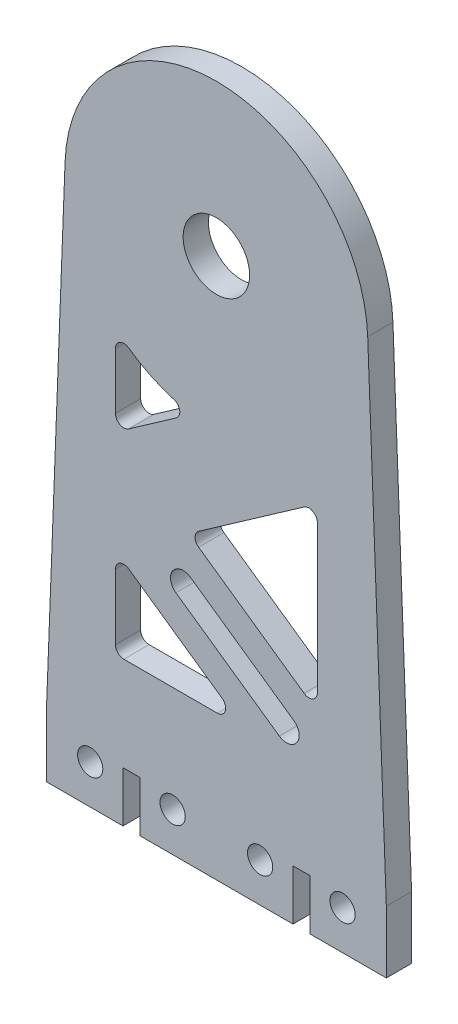
SolidWorks part; units mm, degrees
material "Acrylic (Medium-high impact)"
ref_plane "Front Plane" through (0, 0, 0) normal (0, 0, 1) x (1, 0, 0)
ref_plane "Top Plane" through (0, 0, 0) normal (0, 1, 0) x (1, 0, 0)
ref_plane "Right Plane" through (0, 0, 0) normal (1, 0, 0) x (0, 0, -1)
sketch "Sketch1" plane through (0, 0, 0) normal (0, 0, 1) x (1, 0, 0)
  line L0 (-11.1, 83.4741) -> (-9.1, 83.4741) construction
  line L1 (0, 41.6741) -> (20.2, 41.6741) construction
  line L2 (20.2, 41.6741) -> (20.2, 83.4741) construction
  line L3 (0, 83.4741) -> (9.1, 83.4741)
  line L4 (10.1, 83.4741) -> (10.1, 41.6741) construction
  line L5 (0, 62.5741) -> (20.2, 62.5741) construction
  line L6 (-20.2, 83.4741) -> (-20.2, 41.6741) construction
  line L7 (-20.2, 41.6741) -> (0, 41.6741) construction
  line L8 (-20.2, 83.4741) -> (-11.1, 83.4741)
  line L9 (-10.1, 83.4741) -> (-10.1, 41.6741) construction
  line L10 (-20.2, 62.5741) -> (0, 62.5741) construction
  line L11 (-20.2, 41.6741) -> (-17.9755, -0.9384) construction
  line L12 (20.2, 41.6741) -> (17.9755, -0.9384) construction
  line L13 (0, 0) -> (0, 147.6909) construction
  line L14 (-20.2, 90.8741) -> (-17.9867, 148.3831)
  line L15 (20.2, 90.8741) -> (17.9867, 148.3831)
  line L16 (11.1, 83.4741) -> (20.2, 83.4741)
  line L17 (-11.1, 83.4741) -> (-11.1, 89.4741)
  line L18 (-11.1, 89.4741) -> (-9.1, 89.4741)
  line L19 (-9.1, 83.4741) -> (-9.1, 89.4741)
  line L20 (11.1, 83.4741) -> (9.1, 83.4741) construction
  line L21 (11.1, 83.4741) -> (11.1, 89.4741)
  line L22 (11.1, 89.4741) -> (9.1, 89.4741)
  line L23 (9.1, 83.4741) -> (9.1, 89.4741)
  line L24 (-9.1, 83.4741) -> (0, 83.4741)
  line L25 (-20.2, 90.8741) -> (20.2, 90.8741) construction
  line L26 (-20.2, 83.4741) -> (-20.2, 90.8741)
  line L27 (20.2, 83.4741) -> (20.2, 90.8741)
  circle A0 centre (10.1, 73.3741) radius 6.5 construction
  arc A1 (-17.9755, -0.9384) -> (17.9755, -0.9384) centre (0, 0) cw construction
  circle A2 centre (0, 0) radius 2.5 construction
  arc A3 (-17.9755, -0.9384) -> (17.9755, -0.9384) centre (0, 0) ccw construction
  circle A4 centre (5.2, 88.1241) radius 1.5
  circle A5 centre (15, 88.1241) radius 1.5
  circle A6 centre (-10.1, 51.7741) radius 6.5 construction
  circle A7 centre (-15, 88.1241) radius 1.5
  circle A8 centre (-5.2, 88.1241) radius 1.5
  circle A9 centre (-15, 37.0241) radius 1.5 construction
  circle A10 centre (-5.2, 37.0241) radius 1.5 construction
  circle A11 centre (0, 0) radius 52.75 construction
  circle A12 centre (5.2, 37.0241) radius 1.5 construction
  circle A13 centre (15, 37.0241) radius 1.5 construction
  arc A14 (17.9867, 148.3831) -> (-17.9867, 148.3831) centre (0, 147.6909) ccw
  circle A15 centre (0, 147.6909) radius 3.95
  circle A16 centre (10.1, 73.3741) radius 75 construction
  dimension "D1" = 5
  dimension "D2" = 18
  dimension "D10" = 51.1
  dimension "D3" = 13
  dimension "D4" = 3
  dimension "D8" = 9.8
  dimension "D9" = 105.5
  dimension "D5" = 20.2
  dimension "D19" = 36
  dimension "D20" = 7.9
  dimension "D18" = 150
  dimension "D6" = 10.1
  dimension "D7" = 41.8
  dimension "D13" = 10.1
  dimension "D14" = 6
  dimension "D15" = 9.8
  dimension "D16" = 2
  dimension "D21" = 7.4
extrude "Main Body Link B1" add sketch "Sketch1" along normal blind 3
sketch "Sketch2" plane through (0, 0, 3) normal (0, 0, 1) x (1, 0, 0)
  line L0 (0, 147.6909) -> (0, 83.4741) construction
  line L1 (-12, 134.2745) -> (12, 134.2745) construction
  line L2 (-12, 134.2745) -> (-12, 123.585)
  line L3 (-12, 100.6909) -> (3.2782, 100.6909)
  line L4 (12, 128.1722) -> (12, 106.7932)
  line L5 (-12, 117.4827) -> (12, 117.4827) construction
  line L6 (-12, 111.3804) -> (-12, 100.6909)
  line L7 (12, 100.6909) -> (-12, 117.4827) construction
  line L8 (-12, 117.4827) -> (12, 134.2745) construction
  line L9 (3.2782, 100.6909) -> (-12, 111.3804)
  line L10 (-12, 123.585) -> (-2.9299, 129.9309)
  line L12 (-3.2782, 117.4827) -> (12, 106.7932)
  line L13 (-3.2782, 117.4827) -> (12, 128.1722)
  line L14 (3.2782, 100.6909) -> (12, 100.6909) construction
  line L15 (12, 100.6909) -> (12, 106.7932) construction
  line L16 (-12, 123.585) -> (-12, 117.4827) construction
  line L17 (-12, 117.4827) -> (-12, 111.3804) construction
  line L19 (12, 134.2745) -> (12, 128.1722) construction
  line L20 (-9.1, 83.4741) -> (9.1, 83.4741) construction
  arc A0 (-12, 134.2745) -> (-2.9299, 129.9309) centre (0, 147.6909) ccw
  arc A1 (-17.9867, 148.3831) -> (-12, 134.2745) centre (0, 147.6909) ccw construction
  arc A2 (12, 134.2745) -> (17.9867, 148.3831) centre (0, 147.6909) ccw construction
  arc A3 (17.9867, 148.3831) -> (-17.9867, 148.3831) centre (0, 147.6909) ccw construction
  dimension "D1" = 24
  dimension "D2" = 47
  dimension "D3" = 10
extrude "Cut-Extrude1" cut sketch "Sketch2" against normal up to next contours L13 L12 L4 | A0 L2 L10 | L6 L3 L9
sketch "Sketch3" plane through (0, 0, 3) normal (0, 0, 1) x (1, 0, 0)
  line L0 (-3.9526, 111.8523) -> (8.3378, 103.2531) construction
  line L1 (3.2782, 100.6909) -> (-12, 111.3804) construction
  line L2 (-3.2782, 117.4827) -> (12, 106.7932) construction
  line L3 (3.2782, 100.6909) -> (-12, 111.3804) construction
  line L4 (-3.2782, 117.4827) -> (12, 106.7932) construction
  line L5 (-4.3609, 106.0356) -> (1.3718, 114.2293) construction
  line L6 (-4.8125, 110.6232) -> (7.4779, 102.0241)
  line L7 (-3.0927, 113.0813) -> (9.1977, 104.4822)
  arc A0 (-3.0927, 113.0813) -> (-4.8125, 110.6232) centre (-3.9526, 111.8523) ccw
  arc A1 (7.4779, 102.0241) -> (9.1977, 104.4822) centre (8.3378, 103.2531) ccw
  dimension "D1" = 3
  dimension "D2" = 3
  dimension "D3" = 12
extrude "PulleyIdler" cut sketch "Sketch3" along direction (0, 0, 1) on the side against the normal up to next (3 mm away)
fillet "Fillet1" radius 1 9 edges at (-12, 100.6909, 1.5) (3.2782, 100.6909, 1.5) (-12, 111.3804, 1.5) (12, 106.7932, 1.5) (12, 128.1722, 1.5) (-3.2782, 117.4827, 1.5) (-12, 123.585, 1.5) (-2.9299, 129.9309, 1.5) (-12, 134.2745, 1.5)
equation "\"D20@Sketch1\"=8-\"radii_fit@Parameters@Parameters.SLDPRT\""
equation "\"D18@Sketch1\"=\"CenterDist3@Parameters@Parameters.SLDPRT\"*2"
equation "\"D9@Sketch1\"=\"CenterDist2@Parameters@Parameters.SLDPRT\"*2"
